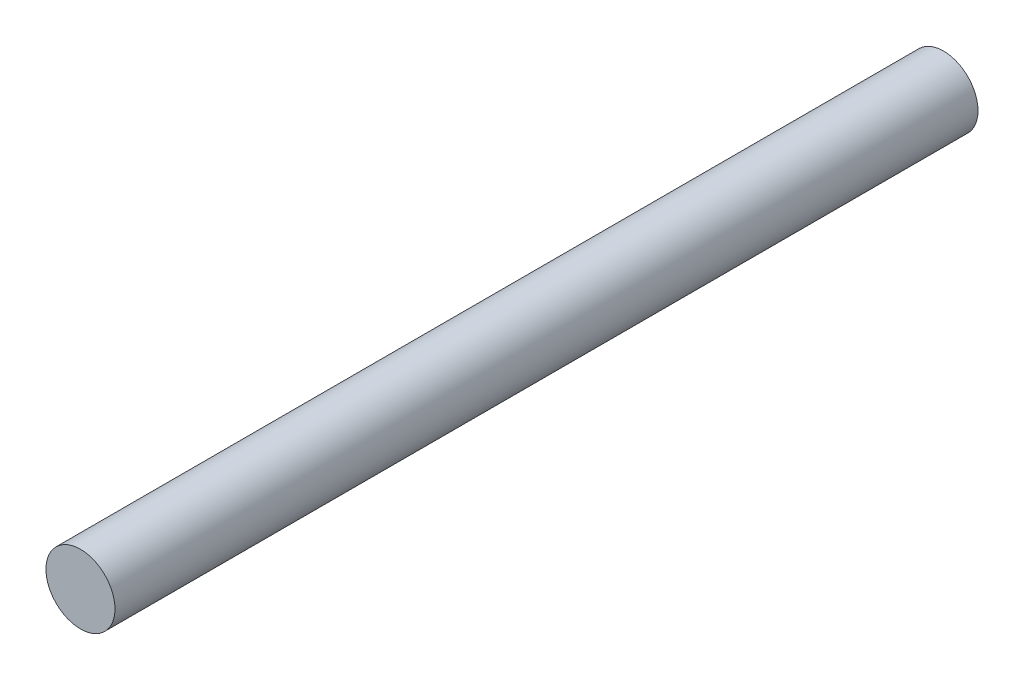
SolidWorks part; units mm, degrees
ref_plane "Front Plane" through (0, 0, 0) normal (0, 0, 1) x (1, 0, 0)
ref_plane "Top Plane" through (0, 0, 0) normal (0, 1, 0) x (1, 0, 0)
ref_plane "Right Plane" through (0, 0, 0) normal (1, 0, 0) x (0, 0, -1)
sketch "Sketch1" plane through (0, 0, 0) normal (0, 0, 1) x (1, 0, 0)
  circle A0 centre (0, 0) radius 3
  dimension "D1" = 6
extrude "Boss-Extrude1" add sketch "Sketch1" along normal blind 75
cosmetic thread "Cosmetic Thread1" parameters "D2"=4.773
equation "\"CarriageWidth\"=56"
equation "\"D1@Boss-Extrude1\"= \"CarriageWidth\" + 10 + 8 + 1 'mount width and cog + stopper width + space for cog to rotate freely"
